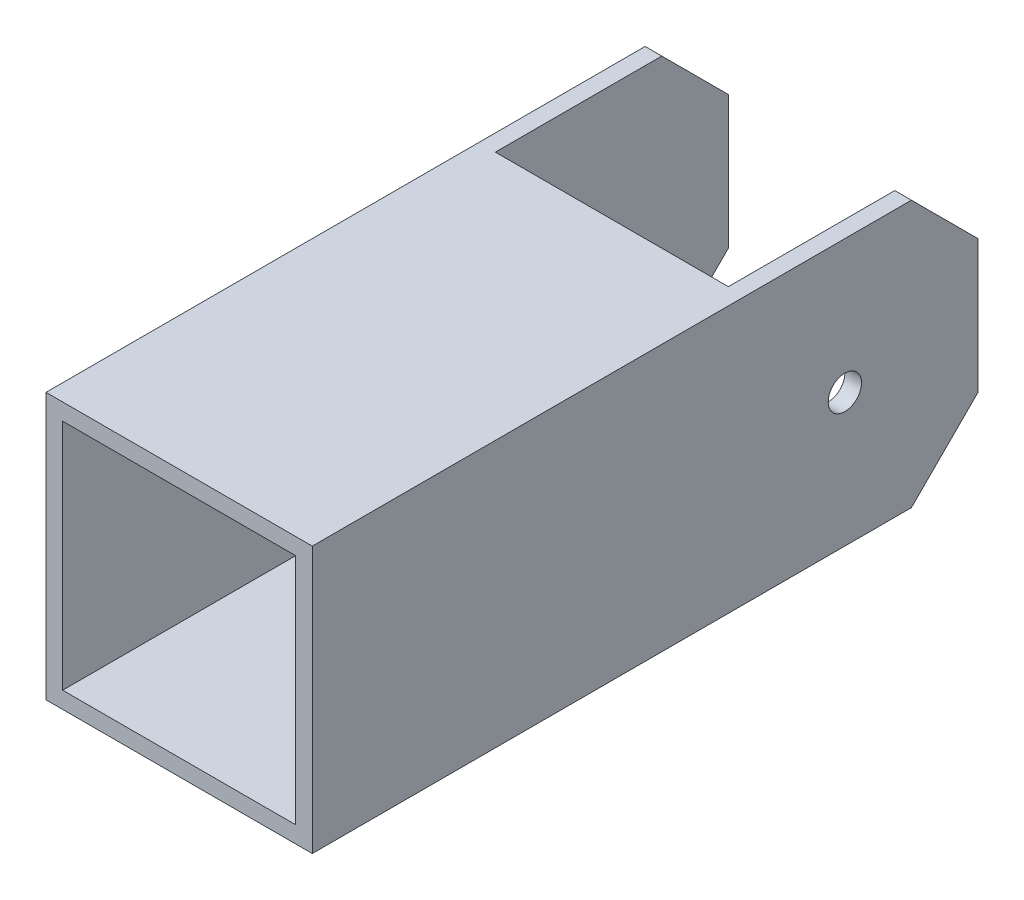
SolidWorks part; units mm, degrees
ref_plane "Front Plane" through (0, 0, 0) normal (0, 0, 1) x (1, 0, 0)
ref_plane "Top Plane" through (0, 0, 0) normal (0, 1, 0) x (1, 0, 0)
ref_plane "Right Plane" through (0, 0, 0) normal (1, 0, 0) x (0, 0, -1)
sketch "Sketch2" plane through (0, 0, 0) normal (0, 0, 1) x (1, 0, 0)
  line L1 (-25.4, 25.4) -> (25.4, 25.4)
  line L2 (-25.4, 25.4) -> (-25.4, -25.4)
  line L3 (-25.4, -25.4) -> (25.4, -25.4)
  line L4 (25.4, 25.4) -> (25.4, -25.4)
  line L5 (-25.4, 25.4) -> (25.4, -25.4) construction
  line L6 (-25.4, -25.4) -> (25.4, 25.4) construction
  line L7 (-22.225, 22.225) -> (22.225, 22.225)
  line L8 (-22.225, 22.225) -> (-22.225, -22.225)
  line L9 (-22.225, -22.225) -> (22.225, -22.225)
  line L10 (22.225, 22.225) -> (22.225, -22.225)
  line L11 (-22.225, 22.225) -> (22.225, -22.225) construction
  line L12 (-22.225, -22.225) -> (22.225, 22.225) construction
  point P0 (0, 0)
  point P6 (0, 0)
  dimension "D1" = 50.8
  dimension "D2" = 50.8
  dimension "D3" = 44.45
  dimension "D4" = 44.45
extrude "Boss-Extrude1" add sketch "Sketch2" along normal blind 127
sketch "Sketch3" plane through (-25.4, 0, 0) normal (-1, 0, 0) x (0, 0, 1)
  line L0 (127, 0) -> (0, 0) construction
  line L1 (127, 25.4) -> (127, -25.4) construction
  line L2 (0, 25.4) -> (0, -25.4) construction
  circle A0 centre (25.4, 0) radius 3.175
  dimension "D1" = 6.35
  dimension "D2" = 25.4
extrude "Cut-Extrude1" cut sketch "Sketch3" against normal through all
sketch "Sketch5" plane through (0, 25.4, 0) normal (0, 1, 0) x (1, 0, 0)
  line L0 (25.4, 0) -> (-25.4, 0) construction
  line L1 (22.225, 0) -> (-22.225, 0)
  line L2 (22.225, 0) -> (22.225, -44.45)
  line L3 (22.225, -44.45) -> (-22.225, -44.45)
  line L4 (-22.225, 0) -> (-22.225, -44.45)
  line L5 (-25.4, -127) -> (-25.4, 0) construction
  line L6 (25.4, -127) -> (25.4, 0) construction
  point P6 (-22.225, -22.225)
  dimension "D1" = 3.175
  dimension "D2" = 3.175
  dimension "D3" = 44.45
extrude "Cut-Extrude2" cut sketch "Sketch5" against normal through all
chamfer "Chamfer1" distance 12.7 angle 45 4 edges at (23.8125, 25.4, 0) (-23.8125, 25.4, 0) (-23.8125, -25.4, 0) (23.8125, -25.4, 0)
